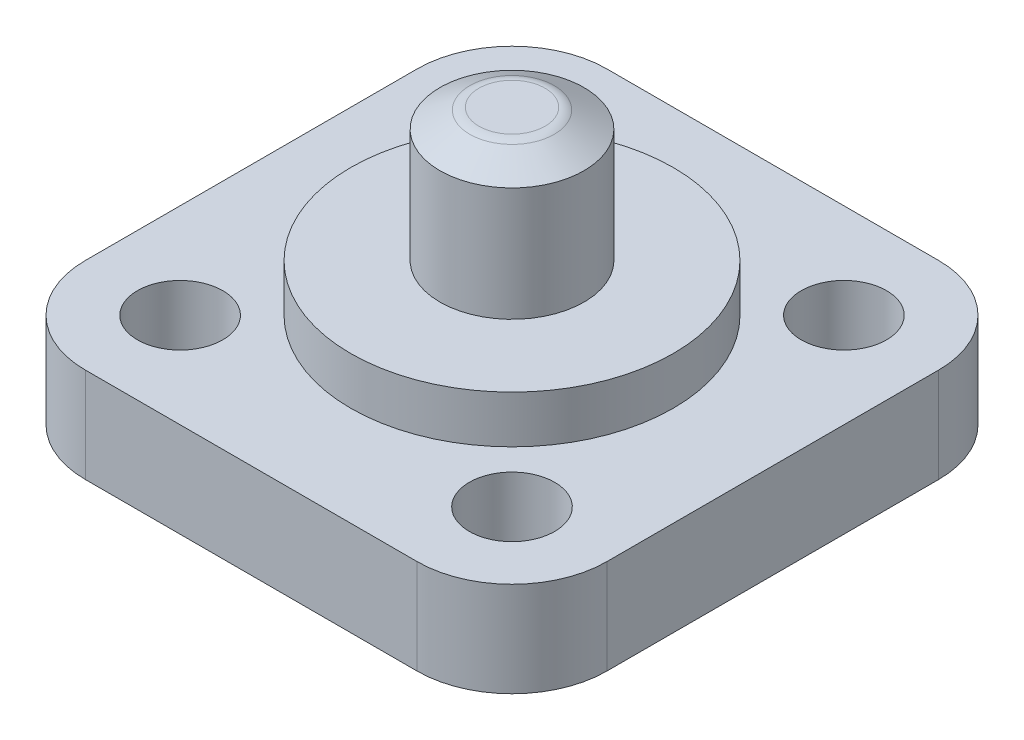
SolidWorks part; units mm, degrees
ref_plane "Front Plane" through (0, 0, 0) normal (0, 0, 1) x (1, 0, 0)
ref_plane "Top Plane" through (0, 0, 0) normal (0, 1, 0) x (1, 0, 0)
ref_plane "Right Plane" through (0, 0, 0) normal (1, 0, 0) x (0, 0, -1)
sketch "Sketch1" plane through (0, 0, 0) normal (0, 0, 1) x (1, 0, 0)
  line L0 (0, 9.5) -> (0, -9.5) construction
  line L1 (0, 9.5) -> (3.4817, 9.5)
  line L2 (4.453, 9.2483) -> (7.6, 7.5)
  line L3 (7.6, 7.5) -> (7.6, -4.5)
  line L4 (7.6, -9.5) -> (0, -9.5)
  line L5 (0, 9.5) -> (0, -9.5)
  line L6 (7.6, -4.5) -> (17, -4.5)
  line L7 (17, -4.5) -> (17, -9.5)
  line L8 (17, -9.5) -> (7.6, -9.5)
  arc A0 (3.4817, 9.5) -> (4.453, 9.2483) centre (3.4817, 7.5) cw
  point P4 (0, 0)
  point P10 (4, 9.5)
  dimension "D5" = 2
  dimension "D1" = 17
  dimension "D2" = 2
  dimension "D3" = 15.2
  dimension "D4" = 4
  dimension "D6" = 17
  dimension "D7" = 5
revolve "Revolve1" add sketch "Sketch1" angle 360 about L0
sketch "Sketch2" plane through (0, -9.5, 0) normal (0, -1, 0) x (1, 0, 0)
  line L0 (27.5, 27.5) -> (-27.5, -27.5) construction
  line L1 (17.5, 27.5) -> (-17.5, 27.5)
  line L2 (27.5, 17.5) -> (27.5, -17.5)
  line L3 (17.5, -27.5) -> (-17.5, -27.5)
  line L4 (-27.5, 17.5) -> (-27.5, -17.5)
  arc A0 (-17.5, 27.5) -> (-27.5, 17.5) centre (-17.5, 17.5) ccw
  arc A1 (-17.5, -27.5) -> (-27.5, -17.5) centre (-17.5, -17.5) cw
  arc A2 (27.5, -17.5) -> (17.5, -27.5) centre (17.5, -17.5) cw
  arc A3 (17.5, 27.5) -> (27.5, 17.5) centre (17.5, 17.5) cw
  dimension "D2" = 10
  dimension "D1" = 55
extrude "Boss-Extrude1" add sketch "Sketch2" along normal blind 10
sketch "Sketch3" plane through (0, -9.5, 0) normal (0, 1, 0) x (1, 0, 0)
  circle A0 centre (-17.5, 17.5) radius 4.5
  dimension "D1" = 9
extrude "Cut-Extrude1" cut sketch "Sketch3" against normal through all
mirror "Mirror1" about plane through (0, 0, 0) normal (0, 0, 1) of "Cut-Extrude1" second plane through (0, 0, 0) second plane normal (1, 0, 0)
